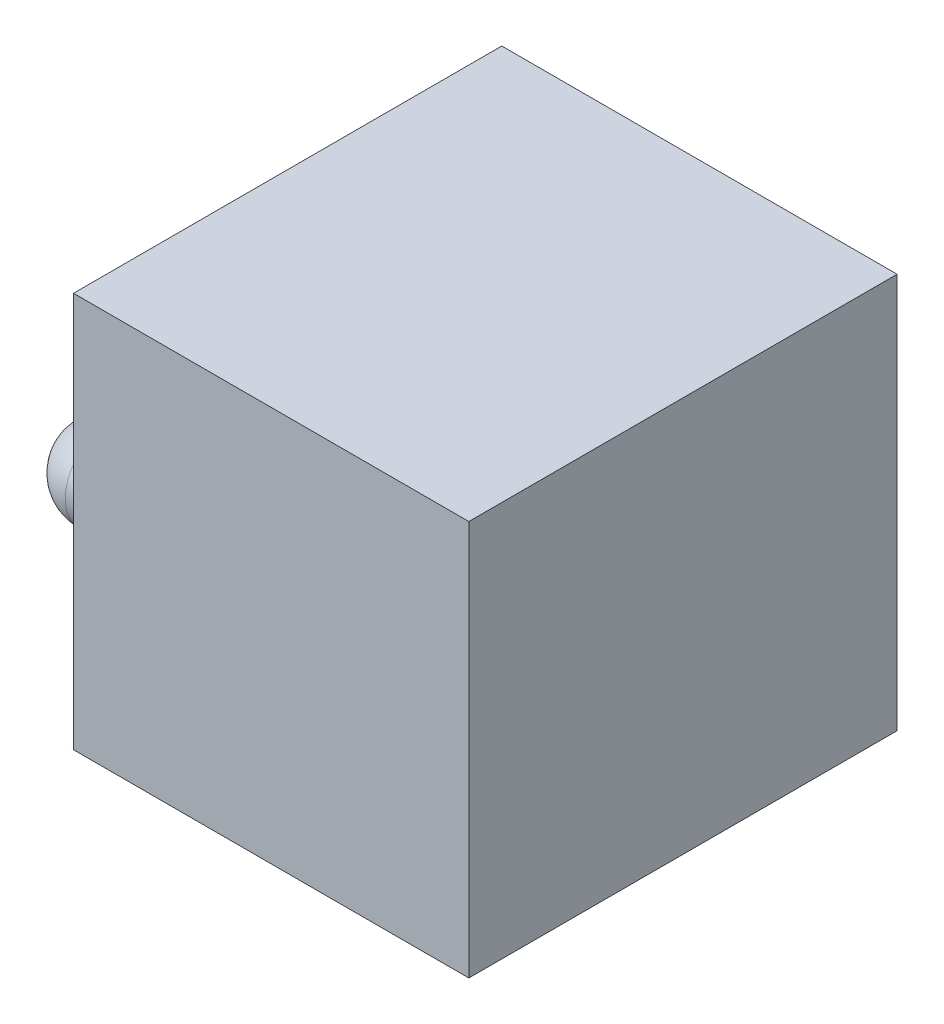
SolidWorks part; units mm, degrees
ref_plane "Front Plane" through (0, 0, 0) normal (0, 0, 1) x (1, 0, 0)
ref_plane "Top Plane" through (0, 0, 0) normal (0, 1, 0) x (1, 0, 0)
ref_plane "Right Plane" through (0, 0, 0) normal (1, 0, 0) x (0, 0, -1)
sketch "Sketch1" plane through (0, 0, 0) normal (0, 1, 0) x (1, 0, 0)
  line L1 (-12, -13) -> (12, -13)
  line L2 (-12, -13) -> (-12, 13)
  line L3 (-12, 13) -> (12, 13)
  line L4 (12, -13) -> (12, 13)
  line L5 (-12, -13) -> (12, 13) construction
  line L6 (-12, 13) -> (12, -13) construction
  point P0 (0, 0)
  dimension "D1" = 26
  dimension "D2" = 24
extrude "Boss-Extrude1" add sketch "Sketch1" along normal blind 24
sketch "Sketch2" plane through (-12, 0, 0) normal (-1, 0, 0) x (0, 0, 1)
  circle A0 centre (-4.5, 7.1489) radius 2.7
  dimension "D1" = 5.4
  dimension "D2" = 4.5
extrude "Boss-Extrude2" add sketch "Sketch2" along normal blind 9
fillet "Fillet2" radius 2.7 1 edges at (-21, 7.1489, -1.8)
mirror "Mirror2" about plane through (0, 0, 0) normal (0, 0, 1) of "Fillet2", "Boss-Extrude2"
equation "\"rail width\"= 24"
equation "\"system width\"= 125"
equation "\"system depth\"= 250"
equation "\"internal height\"= 100"
equation "\"carriage height\"= 24"
equation "\"belt width\"= 6"
equation "\"worm gear diameter\"= 8"
equation "\"D1@Sketch1\"=\"rail width\"+2"
equation "\"D2@Sketch1\"=\"rail width\""
equation "\"D1@Boss-Extrude1\"=\"carriage height\""
equation "\"pin spacing\"= 9"
equation "\"pin radius\"= 2.7"
equation "\"D1@Sketch2\"=\"pin radius\"*2"
equation "\"D2@Sketch2\"=\"pin spacing\"/2"
equation "\"D1@Boss-Extrude2\"=\"pin spacing\""
equation "\"D1@Fillet2\"=\"pin radius\""
